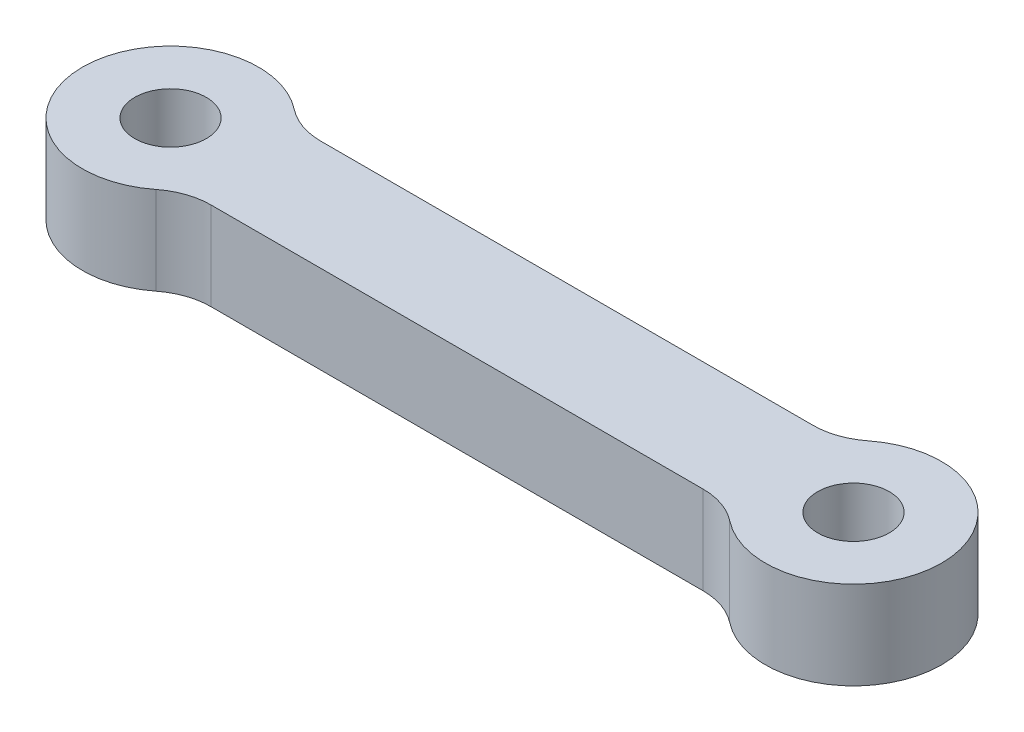
SolidWorks part; units mm, degrees
other "Markup1"
sketch "Sketch2" plane through (-4, 4, -4) normal (-0.0098, 0.9999, -0.0082) x (0.9574, 0.0117, 0.2884)
material "NEOPRENE"
ref_plane "Front Plane" through (0, 0, 0) normal (0, 0, 1) x (1, 0, 0)
ref_plane "Top Plane" through (0, 0, 0) normal (0, 1, 0) x (1, 0, 0)
ref_plane "Right Plane" through (0, 0, 0) normal (1, 0, 0) x (0, 0, -1)
sketch "Sketch1" plane through (0, 0, 0) normal (0, 1, 0) x (1, 0, 0)
  line L0 (0, 0) -> (31, 0) construction
  line L1 (3.1225, 2.5) -> (27.8775, 2.5)
  line L2 (3.1225, -2.5) -> (27.8775, -2.5)
  circle A0 centre (0, 0) radius 4
  circle A1 centre (31, 0) radius 4
  circle A2 centre (0, 0) radius 1.625
  circle A3 centre (31, 0) radius 1.625
  dimension "D1" = 8
  dimension "D3" = 8
  dimension "D5" = 3.25
  dimension "D6" = 3.25
  dimension "D2" = 31
  dimension "D4" = 2.5
extrude "Boss-Extrude1" add sketch "Sketch1" along normal blind 4
fillet "Fillet1" radius 3 4 edges at (3.1225, 2, 2.5) (27.8775, 2, 2.5) (27.8775, 2, -2.5) (3.1225, 2, -2.5)
